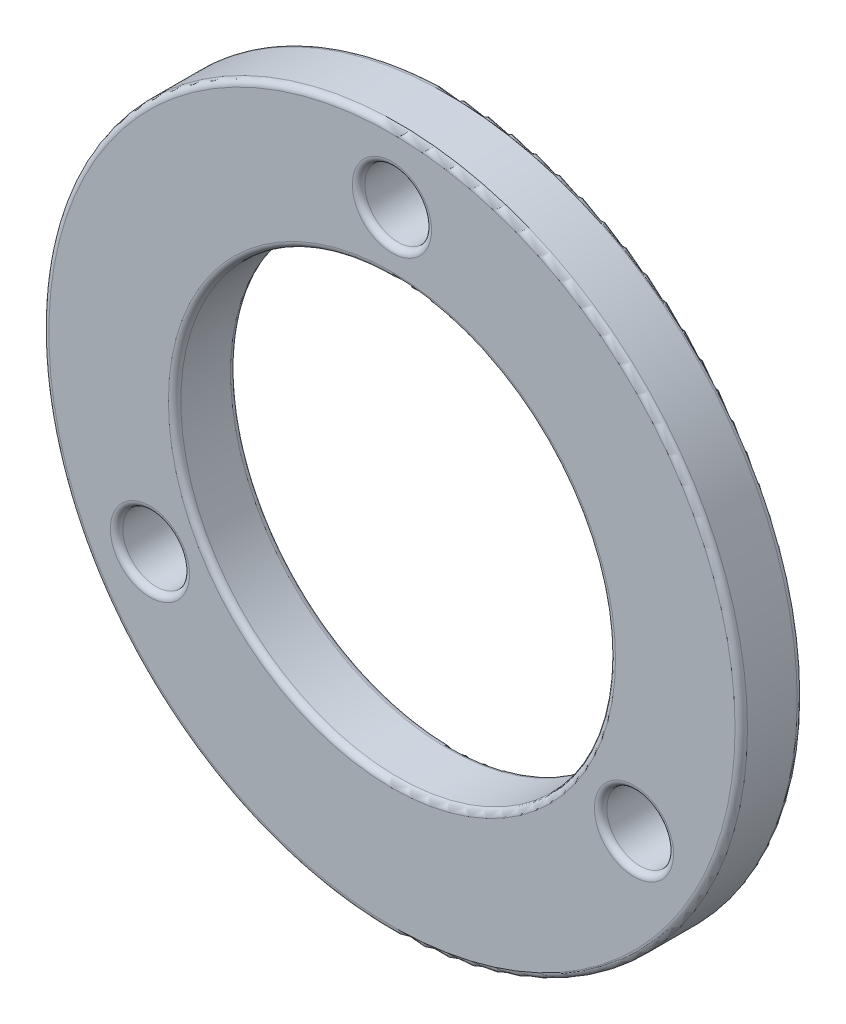
SolidWorks part; units mm, degrees
ref_plane "Front Plane" through (0, 0, 0) normal (0, 0, 1) x (1, 0, 0)
ref_plane "Top Plane" through (0, 0, 0) normal (0, 1, 0) x (1, 0, 0)
ref_plane "Right Plane" through (0, 0, 0) normal (1, 0, 0) x (0, 0, -1)
sketch "Sketch1" plane through (0, 0, 0) normal (0, 0, 1) x (1, 0, 0)
  circle A0 centre (0, 0) radius 112.5
  circle A2 centre (0, 90) radius 10.75
  circle A6 centre (77.9423, -45) radius 10.75
  circle A7 centre (-77.9423, -45) radius 10.75
  circle A8 centre (0, 0) radius 70
  point P11 (0, 0)
  point P15 (0, 0)
  dimension "D2" = 21.5
  dimension "D3" = 225
  dimension "D5" = 140
  dimension "D1" = 90
  dimension "D4" = 3
extrude "Boss-Extrude1" add sketch "Sketch1" along normal blind 20
fillet "Fillet8" radius 2 10 edges at (88.6923, -45, 0) (10.75, 90, 0) (-67.1923, -45, 0) (-67.1923, -45, 20) (10.75, 90, 20) (88.6923, -45, 20) (70, 0, 0) (112.5, 0, 0) (70, 0, 20) (112.5, 0, 20)
